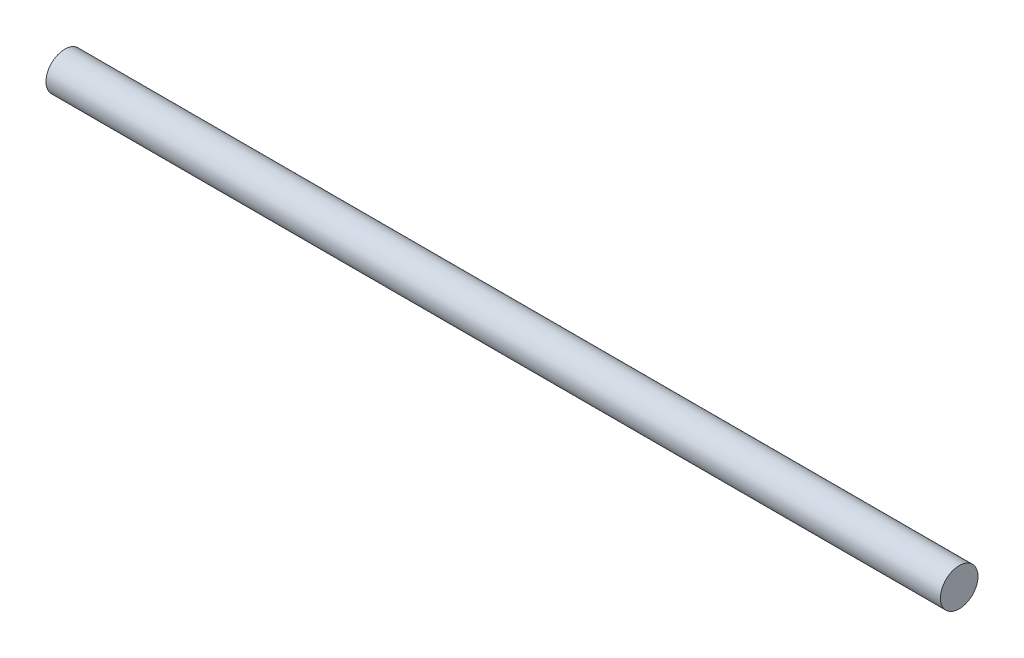
SolidWorks part; units mm, degrees
ref_plane "Front Plane" through (0, 0, 0) normal (0, 0, 1) x (1, 0, 0)
ref_plane "Top Plane" through (0, 0, 0) normal (0, 1, 0) x (1, 0, 0)
ref_plane "Right Plane" through (0, 0, 0) normal (1, 0, 0) x (0, 0, -1)
sketch "Sketch1" plane through (0, 0, 0) normal (1, 0, 0) x (0, 0, -1)
  circle A0 centre (0, 0) radius 1.25
  dimension "D1" = 2.5
extrude "Boss-Extrude1" add sketch "Sketch1" along normal mid plane 59.5
